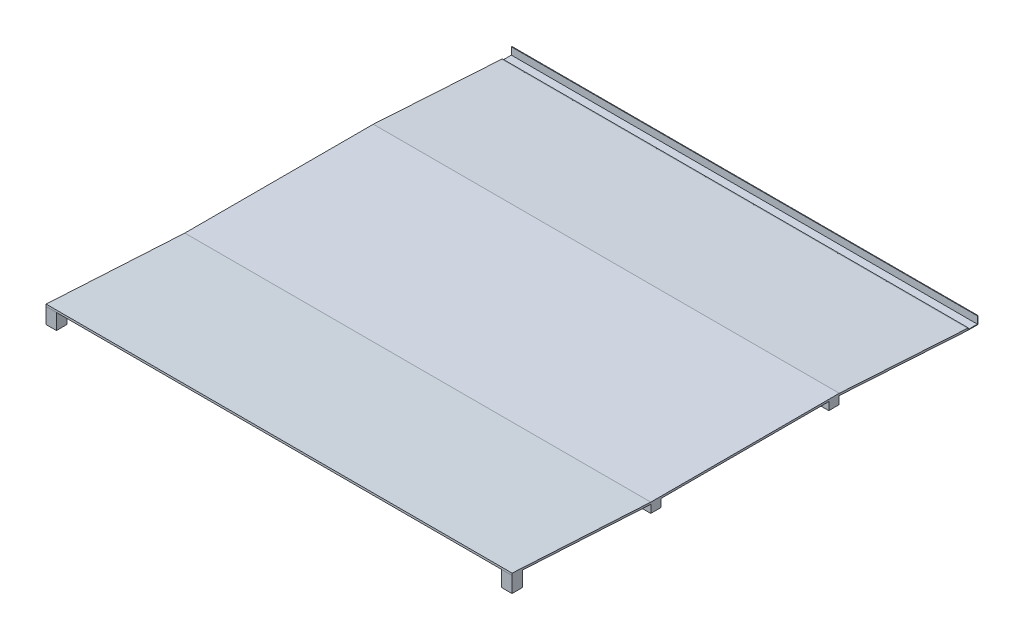
SolidWorks part; units mm, degrees
material "Pine"
ref_plane "Front" through (0, 0, 0) normal (0, 0, 1) x (1, 0, 0)
ref_plane "Top" through (0, 0, 0) normal (0, 1, 0) x (1, 0, 0)
ref_plane "Right" through (0, 0, 0) normal (1, 0, 0) x (0, 0, -1)
sketch "Sketch1" plane through (0, 0, 0) normal (0, 1, 0) x (1, 0, 0)
  line L1 (-2260.6, 2260.6) -> (2260.6, 2260.6) construction
  line L2 (-2260.6, 2260.6) -> (-2260.6, -2260.6) construction
  line L3 (-2260.6, -2260.6) -> (2260.6, -2260.6) construction
  line L4 (2260.6, 2260.6) -> (2260.6, -2260.6) construction
  line L5 (-2260.6, 2260.6) -> (2260.6, -2260.6) construction
  line L6 (-2260.6, -2260.6) -> (2260.6, 2260.6) construction
  point P0 (0, 0)
  dimension "D1" = 4521.2
  dimension "D2" = 4521.2
ref_plane "Plane1" through (0, 0, -2260.6) normal (0, 0, 1) x (1, 0, 0)
ref_plane "Plane2" through (0, 0, 2260.6) normal (0, 0, 1) x (1, 0, 0)
ref_plane "Plane3" through (-2260.6, 0, 0) normal (-1, 0, 0) x (0, 0, 1)
ref_plane "Plane4" through (2260.6, 0, 0) normal (-1, 0, 0) x (0, 0, 1)
sketch "Sketch2" plane through (2260.6, 0, 0) normal (-1, 0, 0) x (0, 0, 1)
  line L0 (-2159, 0) -> (-914.4, 76.2)
  line L1 (-2260.6, 0) -> (2260.6, 0) construction
  line L2 (-914.4, 76.2) -> (914.4, 76.2)
  line L3 (914.4, 76.2) -> (2260.6, 152.4)
  line L4 (2260.6, -2486.66) -> (2260.6, 2486.66) construction
  line L5 (2260.6, 0) -> (-2260.6, 0) construction
  line L6 (0, 0) -> (0, 76.2) construction
  line L7 (-2260.6, -2486.66) -> (-2260.6, 2486.66) construction
  point P13 (0, 0)
  point P14 (-2144.3303, 0)
  dimension "D1" = 76.2
  dimension "D2" = 1828.8
  dimension "D3" = 3.24
  dimension "D4" = 101.6
extrude "Extrude-Thin1" add sketch "Sketch2" along normal blind 4521.2 thin thin type one direction reverse wall 19.05
sketch "Sketch3" plane through (0, 0, 0) normal (0, 1, 0) x (1, 0, 0)
  line L1 (2260.6, -2260.6) -> (2159, -2260.6)
  line L2 (2260.6, -2260.6) -> (2260.6, -2159)
  line L3 (2260.6, -2159) -> (2159, -2159)
  line L4 (2159, -2260.6) -> (2159, -2159)
  line L5 (-2260.6, -2260.6) -> (-2159, -2260.6)
  line L6 (-2260.6, -2260.6) -> (-2260.6, -2159)
  line L7 (-2260.6, -2159) -> (-2159, -2159)
  line L8 (-2159, -2260.6) -> (-2159, -2159)
  line L9 (-2260.6, -914.4) -> (-2159, -914.4)
  line L10 (-2260.6, -914.4) -> (-2260.6, -812.8)
  line L11 (-2260.6, -812.8) -> (-2159, -812.8)
  line L12 (-2159, -914.4) -> (-2159, -812.8)
  line L13 (-2260.6, 914.4) -> (-2159, 914.4)
  line L14 (-2260.6, 914.4) -> (-2260.6, 812.8)
  line L15 (-2260.6, 812.8) -> (-2159, 812.8)
  line L16 (-2159, 914.4) -> (-2159, 812.8)
  line L17 (2260.6, 914.4) -> (2159, 914.4)
  line L18 (2260.6, 914.4) -> (2260.6, 812.8)
  line L19 (2260.6, 812.8) -> (2159, 812.8)
  line L20 (2159, 914.4) -> (2159, 812.8)
  line L21 (2260.6, -914.4) -> (2159, -914.4)
  line L22 (2260.6, -914.4) -> (2260.6, -812.8)
  line L23 (2260.6, -812.8) -> (2159, -812.8)
  line L24 (2159, -914.4) -> (2159, -812.8)
  dimension "D1" = 101.6
extrude "Boss-Extrude1" add sketch "Sketch3" along normal up to surface (76.2 mm away) up to face at (0, 76.2, 0)
sketch "Sketch4" plane through (0, 76.2, 0) normal (0, 1, 0) x (1, 0, 0)
  line L4 (2159, -2260.6) -> (2260.6, -2260.6)
  line L5 (2260.6, -2260.6) -> (2260.6, -2159)
  line L6 (2260.6, -2159) -> (2159, -2159)
  line L7 (2159, -2159) -> (2159, -2260.6)
  line L8 (2159, -2260.6) -> (2260.6, -2260.6)
  line L9 (2260.6, -2260.6) -> (2260.6, -2159)
  line L10 (2260.6, -2159) -> (2159, -2159)
  line L11 (2159, -2159) -> (2159, -2260.6)
  line L12 (-2159, -2159) -> (-2260.6, -2159)
  line L13 (-2260.6, -2159) -> (-2260.6, -2260.6)
  line L14 (-2260.6, -2260.6) -> (-2159, -2260.6)
  line L15 (-2159, -2260.6) -> (-2159, -2159)
  line L16 (-2159, -2159) -> (-2260.6, -2159)
  line L17 (-2260.6, -2159) -> (-2260.6, -2260.6)
  line L18 (-2260.6, -2260.6) -> (-2159, -2260.6)
  line L19 (-2159, -2260.6) -> (-2159, -2159)
  dimension "D1" = 0
  dimension "D2" = 0
extrude "Boss-Extrude2" add sketch "Sketch4" along normal up to surface (70.4491 mm away)
sketch "Sketch5" plane through (-2260.6, 0, 0) normal (-1, 0, 0) x (0, 0, 1)
  line L0 (-2260.6, 76.2) -> (-2260.6, 0)
  line L1 (-2260.6, -2486.66) -> (-2260.6, 2486.66) construction
  line L2 (2260.6, 0) -> (-2260.6, 0) construction
  line L3 (-2260.6, 0) -> (-2160.1641, 0)
  line L4 (-2160.1641, 0) -> (-2160.1641, 19.05)
  line L5 (-2160.1641, 19.05) -> (-2166.5141, 19.05)
  line L6 (-2166.5141, 19.05) -> (-2166.5141, 6.35)
  line L7 (-2166.5141, 6.35) -> (-2254.25, 6.35)
  line L8 (-2254.25, 6.35) -> (-2254.25, 76.2)
  line L9 (-2254.25, 76.2) -> (-2260.6, 76.2)
  line L10 (-2166.5141, 6.35) -> (-2166.5141, 0) construction
  point P14 (-2175.6095, 8.7136)
  dimension "D1" = 6.35
  dimension "D2" = 76.2
  dimension "D3" = 12.7
extrude "Boss-Extrude3" add sketch "Sketch5" against normal up to surface (4521.2 mm away) separate body up to face at (2260.6, 57.9284, 398.7316)
